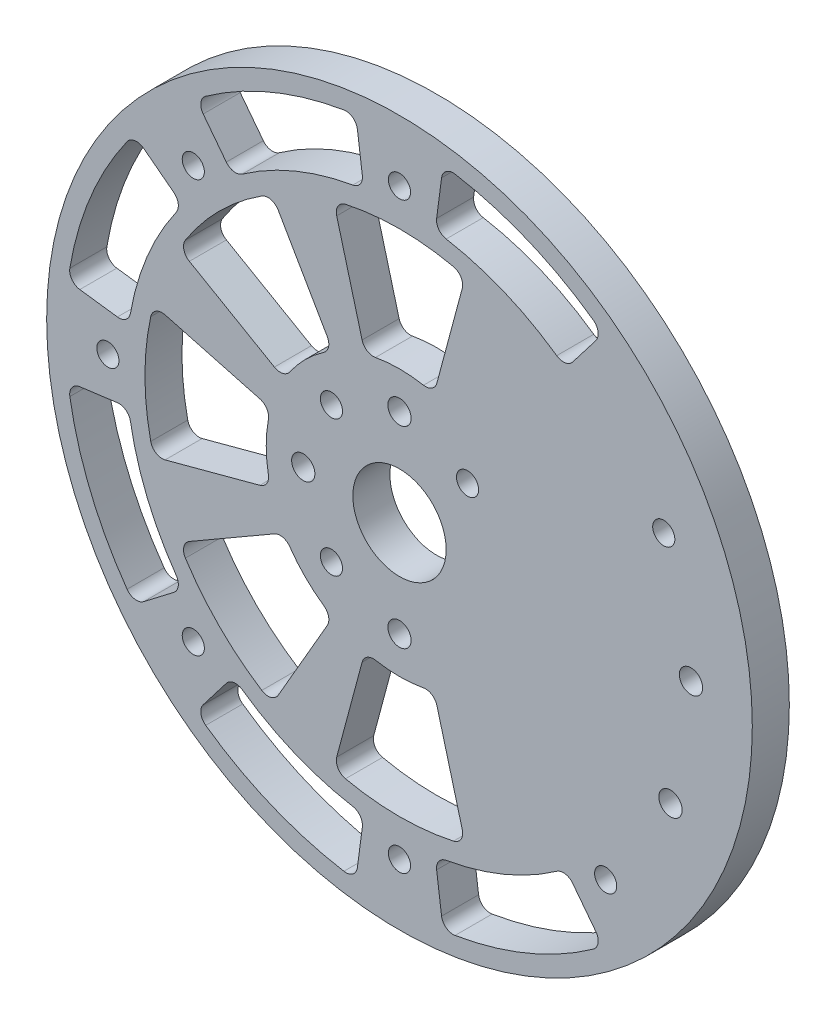
SolidWorks part; units mm, degrees
material "Balsa"
ref_plane "Front Plane" through (0, 0, 0) normal (0, 0, 1) x (1, 0, 0)
ref_plane "Top Plane" through (0, 0, 0) normal (0, 1, 0) x (1, 0, 0)
ref_plane "Right Plane" through (0, 0, 0) normal (1, 0, 0) x (0, 0, -1)
sketch "Sketch1" plane through (0, 0, 0) normal (0, 0, 1) x (1, 0, 0)
  line L0 (45.3154, 21.1309) -> (0, 0) construction
  line L1 (0, 0) -> (35.3553, -35.3553) construction
  line L2 (49.9788, 1.4542) -> (0, 0) construction
  line L3 (0, 0) -> (46.4674, -18.4603) construction
  circle A0 centre (45.3154, 21.1309) radius 1.8986
  circle A1 centre (49.9788, 1.4542) radius 1.9939
  circle A2 centre (0, 0) radius 60.5
  circle A3 centre (0, 0) radius 8
  circle A4 centre (0, 0) radius 16.5 construction
  circle A5 centre (46.4674, -18.4603) radius 1.9939
  circle A6 centre (0, 0) radius 50 construction
  circle A27 centre (0, -16.5) radius 1.9939
  circle A28 centre (11.6673, -11.6673) radius 1.8986 construction
  circle A30 centre (0, -50) radius 1.8986
  circle A31 centre (-16.5, 0) radius 1.9939
  circle A32 centre (-11.6673, -11.6673) radius 1.8986
  circle A33 centre (0, 16.5) radius 1.9939
  circle A34 centre (-11.6673, 11.6673) radius 1.8986
  circle A35 centre (16.5, 0) radius 1.9939 construction
  circle A36 centre (11.6673, 11.6673) radius 1.8986
  circle A38 centre (-35.3553, -35.3553) radius 1.8986
  circle A40 centre (-50, 0) radius 1.8986
  circle A42 centre (-35.3553, 35.3553) radius 1.8986
  circle A44 centre (0, 50) radius 1.8986
  circle A46 centre (35.3553, 35.3553) radius 1.8986 construction
  circle A48 centre (50, 0) radius 1.8986 construction
  circle A50 centre (35.3553, -35.3553) radius 1.8986
  dimension "D1" = 121
  dimension "D4" = 70
  dimension "D6" = 100
  dimension "D7" = 23.333
  dimension "D8" = 33
  dimension "D9" = 3.7973
  dimension "D10" = 3.9878
  dimension "D15" = 3.7973
  dimension "D17" = 3.9878
  dimension "D18" = 3.7973
  dimension "D3" = 16
  dimension "D11" = 3.9878
  dimension "D5" = 23.333
  dimension "D19" = 45
  dimension "D20" = 4
  dimension "D21" = 8
extrude "Boss-Extrude1" add sketch "Sketch1" along normal blind 6.35
sketch "Sketch2" plane through (0, 0, 6.35) normal (0, 0, 1) x (1, 0, 0)
  line L0 (0, 0) -> (-83.0843, 0) construction
  line L1 (-22.0714, 5.914) -> (-42.1627, 11.2975)
  line L2 (-22.0714, -5.914) -> (-42.1627, -11.2975)
  arc A0 (-42.1627, -11.2975) -> (-42.1627, 11.2975) centre (0, 0) cw
  arc A1 (-22.0714, -5.914) -> (-22.0714, 5.914) centre (0, 0) cw
  circle A2 centre (-16.5, 0) radius 1.9939 construction
  circle A3 centre (-50, 0) radius 1.8987 construction
  point P7 (-22.85, 0)
  point P10 (-43.65, 0)
  dimension "D2" = 6.35
  dimension "D3" = 6.35
  dimension "D1" = 30
extrude "Cut-Extrude1" cut sketch "Sketch2" against normal through all
fillet "Fillet1" radius 2 4 edges at (-42.1627, -11.2975, 3.175) (-22.0714, -5.914, 3.175) (-22.0714, 5.914, 3.175) (-42.1627, 11.2975, 3.175)
pattern_circular "CirPattern1" count 8 over 360 about axis through (0, 0, 0) along (0, 0, 1) skipping 3, 4, 5 of "Fillet1", "Cut-Extrude1"
sketch "Sketch3" plane through (0, 0, 6.35) normal (0, 0, 1) x (1, 0, 0)
  line L0 (-83.2273, 0) -> (0, 0) construction
  line L1 (0, 0) -> (-85.2421, 35.3084) construction
  line L2 (-45.479, 34.8972) -> (-37.1488, 28.5053)
  line L3 (-46.4244, 6.1119) -> (-56.8346, 7.4824)
  arc A0 (-56.8346, 7.4824) -> (-45.479, 34.8972) centre (0, 0) cw
  arc A1 (-46.4244, 6.1119) -> (-37.1488, 28.5053) centre (0, 0) cw
  circle A2 centre (-50, 0) radius 1.8987 construction
  circle A3 centre (-50, 0) radius 1.8986 construction
  circle A4 centre (0, 0) radius 60.5 construction
  arc A5 (-42.6565, 9.2598) -> (-42.6565, -9.2598) centre (0, 0) ccw construction
  point P12 (-43.2607, 17.9192)
  dimension "D3" = 3.175
  dimension "D4" = 3.175
  dimension "D1" = 22.5
  dimension "D2" = 30
extrude "Cut-Extrude2" cut sketch "Sketch3" against normal through all
fillet "Fillet2" radius 2 4 edges at (-56.8346, 7.4824, 3.175) (-46.4244, 6.1119, 3.175) (-37.1488, 28.5053, 3.175) (-45.479, 34.8972, 3.175)
pattern_circular "CirPattern3" count 8 over 360 about axis through (0, 0, 0) along (0, 0, 1) skipping 3, 4 of "Cut-Extrude2", "Fillet2"
sketch "Sketch4" plane through (0, 0, 0) normal (0, 0, -1) x (-1, 0, 0)
  circle A0 centre (0, 50) radius 1.8986 construction
  circle A1 centre (35.3553, 35.3553) radius 1.8987 construction
  circle A2 centre (50, 0) radius 1.8987 construction
  circle A3 centre (35.3553, -35.3553) radius 1.8987 construction
  circle A4 centre (0, -50) radius 1.8986 construction
  circle A5 centre (-35.3553, -35.3553) radius 1.8987 construction
  circle A6 centre (-45.3154, 21.1309) radius 1.8987 construction
  circle A7 centre (0, 50) radius 1.8986
  circle A8 centre (35.3553, 35.3553) radius 1.8986
  circle A9 centre (50, 0) radius 1.8986
  circle A10 centre (35.3553, -35.3553) radius 1.8986
  circle A11 centre (0, -50) radius 1.8986
  circle A12 centre (-35.3553, -35.3553) radius 1.8986
  circle A13 centre (-45.3154, 21.1309) radius 1.8986
  circle A14 centre (0, 50) radius 4.7625
  circle A15 centre (35.3553, 35.3553) radius 4.7625
  circle A16 centre (50, 0) radius 4.7625
  circle A17 centre (35.3553, -35.3553) radius 4.7625
  circle A18 centre (0, -50) radius 4.7625
  circle A19 centre (-35.3553, -35.3553) radius 4.7625
  circle A20 centre (-45.3154, 21.1309) radius 4.7625
  dimension "D1" = 9.525
extrude "Cut-Extrude3" cut sketch "Sketch4" against normal blind 3.5719
